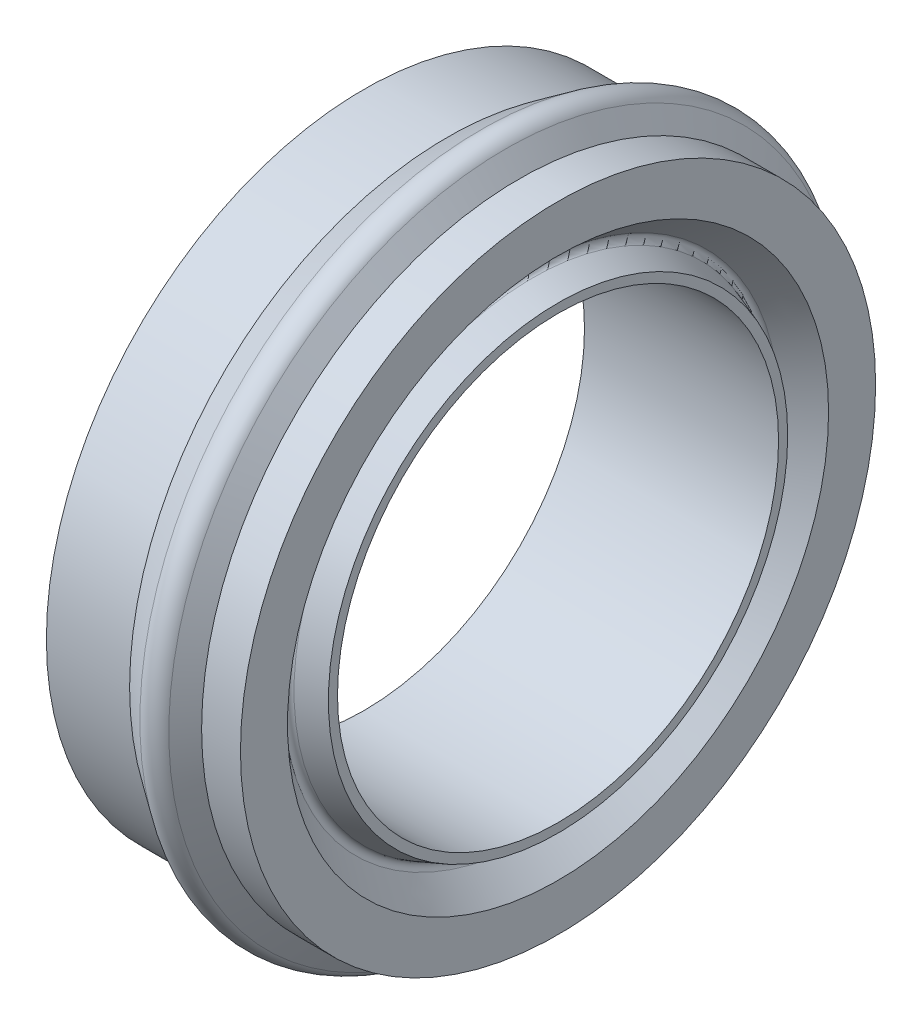
SolidWorks part; units mm, degrees
ref_plane "Alzado" through (0, 0, 0) normal (0, 0, 1) x (1, 0, 0)
ref_plane "Planta" through (0, 0, 0) normal (0, 1, 0) x (1, 0, 0)
ref_plane "Vista lateral" through (0, 0, 0) normal (1, 0, 0) x (0, 0, -1)
sketch "Croquis1" plane through (0, 0, 0) normal (0, 0, 1) x (1, 0, 0)
  line L0 (23.8432, 18) -> (21.6415, 18)
  line L1 (12.8432, 18) -> (12.8432, 16.7822)
  line L2 (29.1158, 0) -> (0, 0) construction
  line L4 (17.5599, 18) -> (19.4851, 19.3432)
  line L5 (20.8774, 19.0952) -> (21.6415, 18)
  line L6 (0, 0) -> (0, 12.4717) construction
  line L7 (12.8432, 12.5) -> (23.8432, 12.5)
  line L8 (23.8432, 12.5) -> (23.8432, 13.0171)
  line L9 (12.8432, 16.7822) -> (15.2397, 14.6722)
  line L10 (15.0509, 13.8174) -> (12.8432, 13.1657)
  line L11 (12.8432, 13.1657) -> (12.8432, 12.5)
  line L12 (23.8432, 15.3339) -> (22.3229, 14.0463)
  line L13 (22.4145, 13.5354) -> (23.8432, 13.0171)
  line L14 (23.8432, 15.3339) -> (23.8432, 18)
  line L15 (17.5599, 18) -> (12.8432, 18)
  arc A0 (20.8774, 19.0952) -> (19.4851, 19.3432) centre (20.0573, 18.523) ccw
  arc A1 (15.2397, 14.6722) -> (15.0509, 13.8174) centre (14.9093, 14.2969) cw
  arc A2 (22.3229, 14.0463) -> (22.4145, 13.5354) centre (22.5168, 13.8174) ccw
  dimension "D3" = 0.5
  dimension "D4" = 0.3
  dimension "D1" = 11
  dimension "D2" = 25
revolve "Revolución1" add sketch "Croquis1" angle 360 about L2
